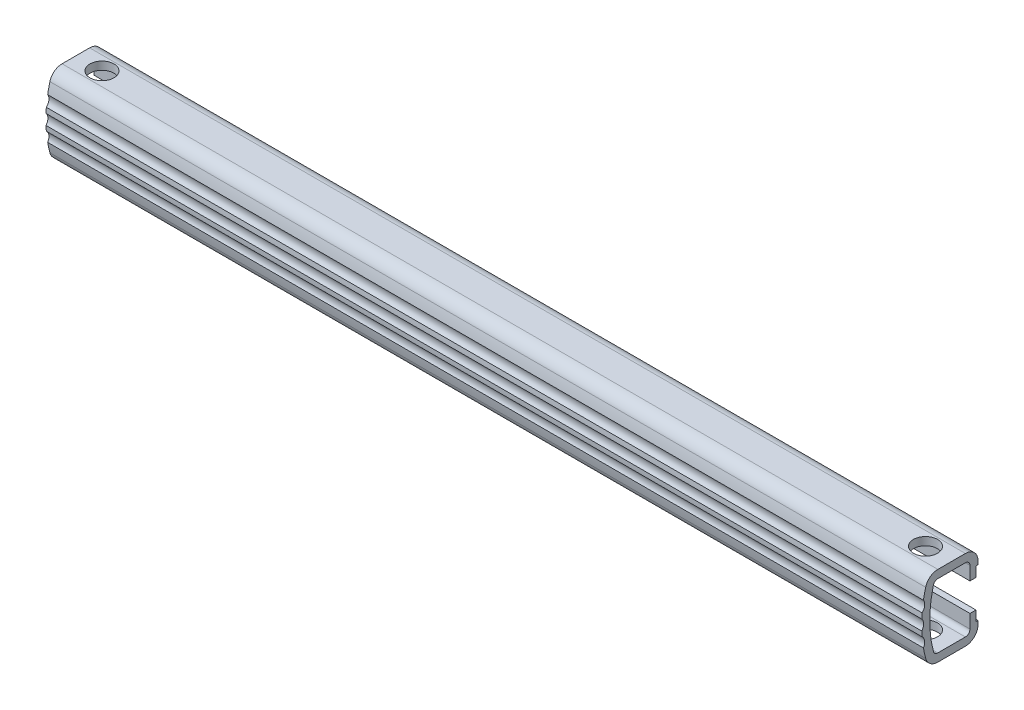
SolidWorks part; units mm, degrees
ref_plane "Front Plane" through (0, 0, 0) normal (0, 0, 1) x (1, 0, 0)
ref_plane "Top Plane" through (0, 0, 0) normal (0, 1, 0) x (1, 0, 0)
ref_plane "Right Plane" through (0, 0, 0) normal (1, 0, 0) x (0, 0, -1)
sketch "Sketch1" plane through (0, 0, 0) normal (1, 0, 0) x (0, 0, -1)
  line L0 (0, 0) -> (-81.198, 0) construction
  line L1 (-1.716, 5) -> (1.716, 5)
  line L2 (3.284, 3.432) -> (3.284, -3.432)
  line L3 (-1.716, -5) -> (1.716, -5)
  line L4 (11.2701, 0) -> (-3.9571, 4.0242) construction
  line L5 (-1.716, 4) -> (1.716, 4)
  line L6 (2.284, 3.432) -> (2.284, -3.432)
  line L7 (11.2701, 0) -> (-3.9571, -4.0242) construction
  line L8 (-1.716, -4) -> (1.716, -4)
  arc A0 (-3.716, 0.6453) -> (-3.716, -0.6453) centre (-4.4799, 0) cw
  arc A1 (-3.232, 3.8326) -> (-1.716, 5) centre (-1.716, 3.432) cw
  arc A2 (1.716, 5) -> (3.284, 3.432) centre (1.716, 3.432) cw
  arc A3 (-3.6742, 1.2906) -> (-3.508, 2.5706) centre (-4.3486, 2.029) ccw
  arc A4 (-3.508, 2.5706) -> (-3.232, 3.8326) centre (11.2701, 0) cw
  arc A5 (-3.716, 0.6453) -> (-3.6742, 1.2906) centre (11.2701, 0) cw
  arc A6 (-3.716, -0.6453) -> (-3.6742, -1.2906) centre (11.2701, 0) ccw
  arc A7 (-3.508, -2.5706) -> (-3.232, -3.8326) centre (11.2701, 0) ccw
  arc A8 (-3.6742, -1.2906) -> (-3.508, -2.5706) centre (-4.3486, -2.029) cw
  arc A9 (1.716, -5) -> (3.284, -3.432) centre (1.716, -3.432) ccw
  arc A10 (-3.232, -3.8326) -> (-1.716, -5) centre (-1.716, -3.432) ccw
  arc A11 (-4.4799, 0) -> (-3.9571, 4.0242) centre (11.2701, 0) cw construction
  arc A12 (-2.2652, -3.5771) -> (-2.2652, 3.5771) centre (11.2701, 0) cw
  arc A13 (-2.2652, 3.5771) -> (-1.716, 4) centre (-1.716, 3.432) cw
  arc A14 (1.716, 4) -> (2.284, 3.432) centre (1.716, 3.432) cw
  arc A15 (1.716, -4) -> (2.284, -3.432) centre (1.716, -3.432) ccw
  arc A16 (-2.2652, -3.5771) -> (-1.716, -4) centre (-1.716, -3.432) ccw
  point P12 (2.284, 0)
  point P13 (0, 5)
  point P29 (-4.3486, 2.029)
  point P36 (0, -5)
  dimension "D1" = 1
  dimension "D2" = 7
  dimension "D5" = 15
  dimension "D6" = 0.75
  dimension "D3" = 5
  dimension "D4" = 10
  dimension "D7" = 1
extrude "Extrude1" add sketch "Sketch1" along normal mid plane 109
sketch "Sketch2" plane through (0, 0, 0) normal (0, 1, 0) x (1, 0, 0)
  line L0 (0, 0) -> (0, -13.5446) construction
  circle A0 centre (-51.25, 0) radius 1.5
  circle A1 centre (51.25, 0) radius 1.5
  dimension "D2" = 3
  dimension "D1" = 102.5
extrude "Cut-Extrude1" cut sketch "Sketch2" against normal through all and the other way through all
sketch "Sketch3" plane through (0, 0, 0) normal (1, 0, 0) x (0, 0, -1)
  line L0 (0, -1.75) -> (0, 1.75)
  line L1 (0, 1.75) -> (3.034, 1.75)
  line L2 (3.034, 1.75) -> (3.034, 3)
  line L3 (3.034, 3) -> (4.284, 3)
  line L4 (4.284, 3) -> (4.284, -3)
  line L5 (0, 0) -> (6.3867, 0) construction
  line L6 (3.034, -3) -> (4.284, -3)
  line L7 (3.034, -1.75) -> (3.034, -3)
  line L8 (0, -1.75) -> (3.034, -1.75)
  line L9 (3.284, -3.432) -> (3.284, 3.432) construction
  point P10 (4.284, 0)
  point P13 (0, 0)
  dimension "D1" = 1
  dimension "D2" = 3.5
  dimension "D3" = 0.25
  dimension "D4" = 1.25
extrude "Cut-Extrude2" cut sketch "Sketch3" against normal through all and the other way through all
